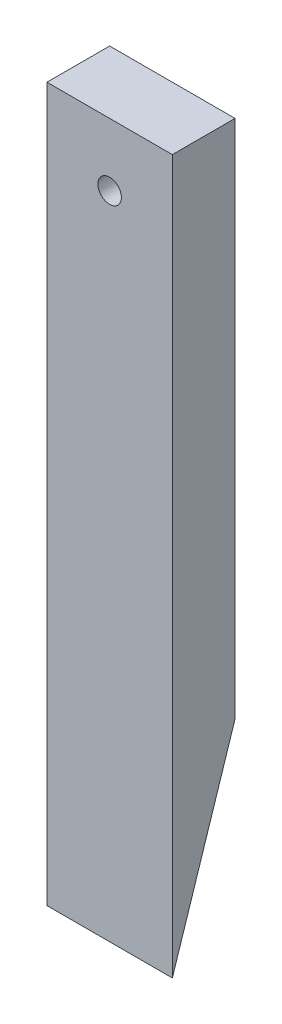
SolidWorks part; units mm, degrees
material "Sapin"
ref_plane "Plan de face" through (0, 0, 0) normal (0, 0, 1) x (1, 0, 0)
ref_plane "Plan de dessus" through (0, 0, 0) normal (0, 1, 0) x (1, 0, 0)
ref_plane "Plan de droite" through (0, 0, 0) normal (1, 0, 0) x (0, 0, -1)
sketch "Esquisse1" plane through (0, 0, 0) normal (0, 0, 1) x (1, 0, 0)
  line L1 (-24, -136.5) -> (24, -136.5)
  line L2 (-24, -136.5) -> (-24, 136.5)
  line L3 (-24, 136.5) -> (24, 136.5)
  line L4 (24, -136.5) -> (24, 136.5)
  line L5 (-24, -136.5) -> (24, 136.5) construction
  line L6 (-24, 136.5) -> (24, -136.5) construction
  point P0 (0, 0)
  dimension "D1" = 48
  dimension "D2" = 273
extrude "Boss.-Extru.1" add sketch "Esquisse1" along normal blind 24
sketch "Esquisse4" plane through (24, 0, 0) normal (1, 0, 0) x (0, 0, -1)
  line L0 (-24, -136.5) -> (0, -62.6356)
  line L1 (0, -136.5) -> (0, 136.5) construction
  line L2 (0, -62.6356) -> (0, -136.5)
  line L3 (0, -136.5) -> (-24, -136.5)
  line L4 (-24, 136.5) -> (0, 136.5) construction
  dimension "D1" = 108
extrude "Enlèv. mat.-Extru.1" cut sketch "Esquisse4" against normal through all
sketch "Esquisse5" plane through (0, 0, 24) normal (0, 0, 1) x (1, 0, 0)
  line L0 (-24, 136.5) -> (24, 88.5) construction
  line L1 (24, -136.5) -> (24, 136.5) construction
  line L2 (-24, 136.5) -> (24, 136.5) construction
  line L3 (24, 136.5) -> (24, 88.5) construction
  circle A0 centre (0, 112.5) radius 4.5
  dimension "D1" = 9
extrude "Enlèv. mat.-Extru.2" cut sketch "Esquisse5" against normal through all
